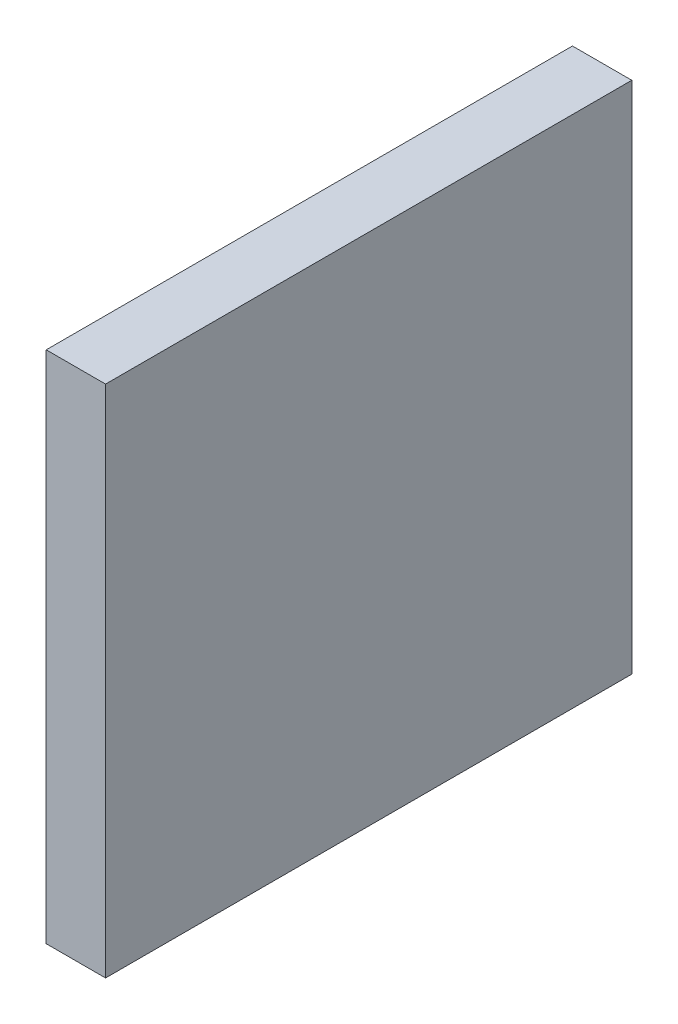
SolidWorks part; units mm, degrees
ref_plane "Front Plane" through (0, 0, 0) normal (0, 0, 1) x (1, 0, 0)
ref_plane "Top Plane" through (0, 0, 0) normal (0, 1, 0) x (1, 0, 0)
ref_plane "Right Plane" through (0, 0, 0) normal (1, 0, 0) x (0, 0, -1)
sketch "Sketch1" plane through (0, 0, 0) normal (1, 0, 0) x (0, 0, -1)
  line L1 (-36.9016, 47.6451) -> (132.0084, 47.6451)
  line L2 (-36.9016, 47.6451) -> (-36.9016, -117.4549)
  line L3 (-36.9016, -117.4549) -> (132.0084, -117.4549)
  line L4 (132.0084, 47.6451) -> (132.0084, -117.4549)
  line L5 (-36.9016, 47.6451) -> (132.0084, -117.4549) construction
  line L6 (-36.9016, -117.4549) -> (132.0084, 47.6451) construction
  point P0 (47.5534, -34.9049)
extrude "Boss-Extrude1" add sketch "Sketch1" along normal blind 19.05 contours L2 L1 L4 L3
